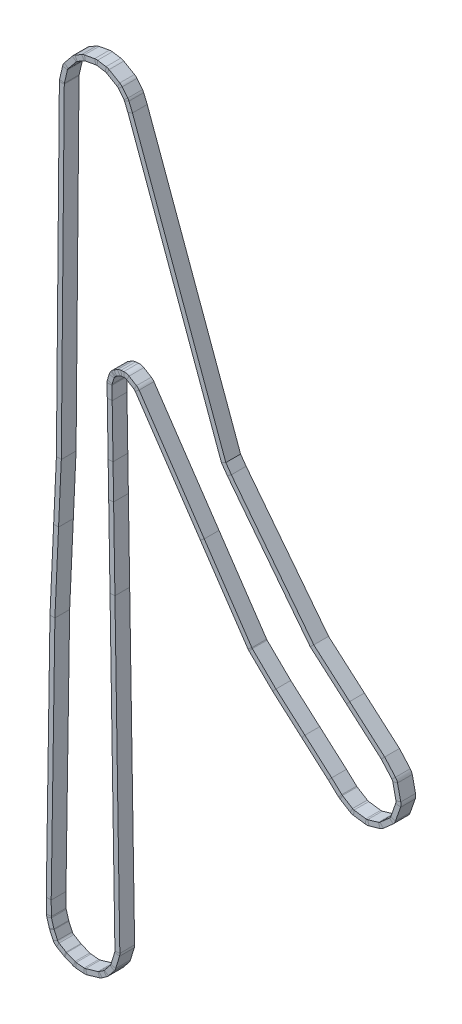
SolidWorks part; units mm, degrees
ref_plane "Front Plane" through (0, 0, 0) normal (0, 0, 1) x (1, 0, 0)
ref_plane "Top Plane" through (0, 0, 0) normal (0, 1, 0) x (1, 0, 0)
ref_plane "Right Plane" through (0, 0, 0) normal (1, 0, 0) x (0, 0, -1)
sketch "Sketch1" plane through (0, 0, 0) normal (0, 0, 1) x (1, 0, 0)
  line L0 (98.4655, -26.6334) -> (45.749, 19.1924)
  line L1 (45.749, 19.1924) -> (0.051, 81.6795)
  line L3 (-7.9905, 92.6754) -> (-68.2589, 257.4582)
  line L4 (-63.2016, 102.3497) -> (12.7547, -10.0268)
  line L5 (12.7547, -10.0268) -> (66.814, -57.6387)
  line L6 (-75.4614, -216.8683) -> (-75.4494, -217.5984)
  line L7 (-119.8994, -217.5984) -> (-117.4111, -51.9664)
  line L8 (-111.3567, 249.8241) -> (-113.2737, 38.7081)
  line L9 (-80.618, 97.0158) -> (-75.4494, -217.5984)
  arc A1 (66.814, -57.6387) -> (98.4655, -26.6334) centre (83.8846, -43.4068) ccw
  arc A2 (-7.9905, 92.6754) -> (0.051, 81.6795) centre (7.6048, 95.6421) ccw
  arc A3 (-68.2589, 257.4582) -> (-111.3567, 249.8241) centre (-89.1317, 249.8241) ccw
  arc A4 (-119.8894, -216.9308) -> (-75.4614, -216.8683) centre (-97.6744, -217.5984) ccw
  arc A5 (-63.2016, 102.3497) -> (-80.618, 97.0158) centre (-71.093, 97.0158) ccw
sketch "Sketch2" plane through (0, 0, 0) normal (0, 1, 0) x (1, 0, 0)
  line L0 (-116.641, -4.7695) -> (-113.466, 4.7555) construction
  line L1 (-113.466, -4.7695) -> (-116.641, -4.7695)
  line L2 (-113.466, -4.7695) -> (-113.466, 4.7555)
  line L3 (-113.466, 4.7555) -> (-116.641, 4.7555)
  line L4 (-116.641, -4.7695) -> (-116.641, 4.7555)
  line L5 (-113.466, -4.7695) -> (-116.641, 4.7555) construction
  dimension "D1" = 3.175
  dimension "D2" = 9.525
sketch "Sketch3" plane through (0, 0, 0) normal (0, 0, 1) x (1, 0, 0)
  line L0 (-113.2737, 38.7081) -> (-111.3607, 249.3794)
  line L1 (-111.2559, 250.2572) -> (-109.2845, 258.7288)
  line L2 (-108.485, 260.36) -> (-103.2826, 266.7567)
  line L3 (-102.1399, 267.7223) -> (-97.7053, 270.2323)
  line L4 (-96.4553, 270.6877) -> (-89.814, 271.9222)
  line L5 (-88.4462, 271.9406) -> (-83.0216, 271.0824)
  line L6 (-81.6152, 270.5801) -> (-74.7314, 266.5543)
  line L7 (-73.5978, 265.5668) -> (-70.0494, 261.0582)
  line L8 (-69.4933, 260.1093) -> (-67.2613, 254.7304)
  line L9 (-7.9905, 92.6754) -> (-68.2589, 257.4582) construction
  line L10 (-67.2613, 254.7304) -> (-6.9418, 89.285)
  line L11 (-6.9418, 89.285) -> (-3.231, 84.0404)
  line L12 (-3.231, 84.0404) -> (50.1017, 15.4087)
  line L13 (98.4655, -26.6334) -> (45.749, 19.1924) construction
  line L14 (50.1017, 15.4087) -> (73.3998, -4.8441)
  line L15 (73.3998, -4.8441) -> (95.8794, -24.3853)
  line L16 (95.8794, -24.3853) -> (102.8247, -32.2162)
  line L17 (103.7499, -34.0415) -> (105.8276, -43.6606)
  line L18 (105.6923, -45.8446) -> (102.428, -55.1766)
  line L19 (101.2968, -56.8629) -> (95.0555, -62.3984)
  line L20 (93.5133, -63.2516) -> (86.4539, -65.3208)
  line L21 (84.7719, -65.4465) -> (77.0991, -64.3963)
  line L22 (75.5267, -63.832) -> (68.9797, -59.7901)
  line L23 (68.3531, -59.3129) -> (61.7508, -53.1793)
  line L24 (12.7547, -10.0268) -> (66.814, -57.6387) construction
  line L25 (61.7508, -53.1793) -> (44.551, -38.0309)
  line L26 (44.551, -38.0309) -> (25.7851, -21.5031)
  line L27 (25.7851, -21.5031) -> (10.5331, -6.5929)
  line L28 (-63.2016, 102.3497) -> (12.7547, -10.0268) construction
  line L29 (10.0108, -5.9672) -> (-20.7003, 39.4696)
  line L30 (-20.7003, 39.4696) -> (-62.7161, 101.6314)
  line L31 (-63.9393, 102.8052) -> (-68.7289, 105.7621)
  line L32 (-71.1857, 106.3495) -> (-73.0015, 106.1972)
  line L33 (-74.6515, 105.6879) -> (-76.8626, 104.4364)
  line L34 (-77.9202, 103.5722) -> (-78.4276, 102.9884)
  line L35 (-79.241, 101.5208) -> (-80.4319, 97.6248)
  line L36 (-80.6076, 96.3791) -> (-80.4673, 87.8427)
  line L37 (-80.618, 97.0158) -> (-75.4494, -217.5984) construction
  line L38 (-80.4673, 87.8427) -> (-79.9113, 53.9988)
  line L39 (-79.9113, 53.9988) -> (-79.5449, 31.6929)
  line L40 (-79.5449, 31.6929) -> (-78.6908, -20.2959)
  line L41 (-78.6908, -20.2959) -> (-75.52, -218.5999)
  line L42 (-75.6957, -219.8437) -> (-78.1516, -227.8785)
  line L43 (-78.8798, -229.2448) -> (-82.5912, -233.8083)
  line L44 (-83.391, -234.5562) -> (-86.3383, -236.6415)
  line L45 (-87.5338, -237.2196) -> (-95.5395, -239.5663)
  line L46 (-97.0156, -239.7148) -> (-102.1926, -239.2755)
  line L47 (-103.3693, -238.9935) -> (-108.7869, -236.7939)
  line L48 (-109.3384, -236.5192) -> (-113.9073, -233.7895)
  line L49 (-115.5023, -232.0146) -> (-117.7346, -227.1706)
  line L50 (-117.9421, -226.6168) -> (-119.5306, -221.1976)
  line L51 (-119.6932, -220.1083) -> (-119.7978, -210.8362)
  line L52 (-119.8994, -217.5984) -> (-117.4111, -51.9664) construction
  line L53 (-119.7978, -210.8362) -> (-117.4111, -51.9664)
  line L54 (-113.2737, 38.7081) -> (-117.4111, -51.9664)
  arc A0 (-68.2589, 257.4582) -> (-111.3567, 249.8241) centre (-89.1317, 249.8241) ccw construction
  arc A1 (-7.9905, 92.6754) -> (0.051, 81.6795) centre (7.6048, 95.6421) ccw construction
  arc A2 (66.814, -57.6387) -> (98.4655, -26.6334) centre (83.8846, -43.4068) ccw construction
  arc A3 (-63.2016, 102.3497) -> (-80.618, 97.0158) centre (-71.093, 97.0158) ccw construction
  arc A4 (-119.8894, -216.9308) -> (-75.4614, -216.8683) centre (-97.6744, -217.5984) ccw construction
  arc A5 (-119.5306, -221.1976) -> (-119.6932, -220.1083) centre (-115.6589, -220.0628) cw
  arc A6 (-117.7346, -227.1706) -> (-117.9421, -226.6168) centre (-114.0704, -225.482) cw
  arc A7 (-113.9073, -233.7895) -> (-115.5023, -232.0146) centre (-111.838, -230.326) cw
  arc A8 (-108.7869, -236.7939) -> (-109.3384, -236.5192) centre (-107.2691, -233.0557) cw
  arc A9 (-102.1926, -239.2755) -> (-103.3693, -238.9935) centre (-101.8515, -235.2553) cw
  arc A10 (-95.5395, -239.5663) -> (-97.0156, -239.7148) centre (-96.6744, -235.6946) cw
  arc A11 (-86.3383, -236.6415) -> (-87.5338, -237.2196) centre (-88.6686, -233.3479) cw
  arc A12 (-82.5912, -233.8083) -> (-83.391, -234.5562) centre (-85.7214, -231.2627) cw
  arc A13 (-78.1516, -227.8785) -> (-78.8798, -229.2448) centre (-82.0099, -226.6991) cw
  arc A14 (-75.52, -218.5999) -> (-75.6957, -219.8437) centre (-79.5541, -218.6644) cw
  arc A15 (10.5331, -6.5929) -> (10.0108, -5.9672) centre (13.3534, -3.7079) cw
  arc A16 (68.9797, -59.7901) -> (68.3531, -59.3129) centre (71.0992, -56.357) cw
  arc A17 (77.0991, -64.3963) -> (75.5267, -63.832) centre (77.6462, -60.3989) cw
  arc A18 (86.4539, -65.3208) -> (84.7719, -65.4465) centre (85.319, -61.4491) cw
  arc A19 (95.0555, -62.3984) -> (93.5133, -63.2516) centre (92.3784, -59.3799) cw
  arc A20 (102.428, -55.1766) -> (101.2968, -56.8629) centre (98.6197, -53.8445) cw
  arc A21 (105.8276, -43.6606) -> (105.6923, -45.8446) centre (101.884, -44.5125) cw
  arc A22 (102.8247, -32.2162) -> (103.7499, -34.0415) centre (99.8062, -34.8933) cw
  arc A23 (-70.0494, 261.0582) -> (-69.4933, 260.1093) centre (-73.2198, 258.563) cw
  arc A24 (-74.7314, 266.5543) -> (-73.5978, 265.5668) centre (-76.7682, 263.0716) cw
  arc A25 (-83.0216, 271.0824) -> (-81.6152, 270.5801) centre (-83.652, 267.0974) cw
  arc A26 (-89.814, 271.9222) -> (-88.4462, 271.9406) centre (-89.0767, 267.9556) cw
  arc A27 (-97.7053, 270.2323) -> (-96.4553, 270.6877) centre (-95.718, 266.7211) cw
  arc A28 (-103.2826, 266.7567) -> (-102.1399, 267.7223) centre (-100.1525, 264.2111) cw
  arc A29 (-109.2845, 258.7288) -> (-108.485, 260.36) centre (-105.3549, 257.8143) cw
  arc A30 (-111.3607, 249.3794) -> (-111.2559, 250.2572) centre (-107.3263, 249.3428) cw
  arc A31 (-80.4319, 97.6248) -> (-80.6076, 96.3791) centre (-76.5735, 96.4454) ccw
  arc A32 (-78.4276, 102.9884) -> (-79.241, 101.5208) centre (-75.3827, 100.3415) ccw
  arc A33 (-76.8626, 104.4364) -> (-77.9202, 103.5722) centre (-74.8752, 100.9252) ccw
  arc A34 (-73.0015, 106.1972) -> (-74.6515, 105.6879) centre (-72.6641, 102.1767) ccw
  arc A35 (-62.7161, 101.6314) -> (-63.9393, 102.8052) centre (-66.0588, 99.3721) ccw
  arc A36 (-68.7289, 105.7621) -> (-71.1857, 106.3495) centre (-70.8484, 102.3291) ccw
  point P83 (-119.6869, -220.6642)
  point P86 (-117.8587, -226.9013)
  point P91 (-109.0732, -236.6777)
  point P94 (-102.8023, -239.2237)
  point P97 (-96.2637, -239.7786)
  point P100 (-86.8878, -237.0303)
  point P103 (-82.9399, -234.2371)
  point P106 (-78.3821, -228.6328)
  point P109 (-75.5098, -219.2356)
  point P112 (10.2402, -6.3066)
  point P115 (68.643, -59.5822)
  point P118 (76.2532, -64.2805)
  point P121 (85.6263, -65.5634)
  point P124 (94.3799, -62.9976)
  point P127 (102.0816, -56.1669)
  point P130 (106.0676, -44.7717)
  point P133 (103.5265, -33.0075)
  point P136 (-69.7061, 260.622)
  point P139 (-74.071, 266.1681)
  point P142 (-82.2711, 270.9637)
  point P145 (-89.1317, 272.0491)
  point P148 (-97.1184, 270.5645)
  point P151 (-102.8023, 267.3473)
  point P154 (-109.0732, 259.6367)
  point P157 (-111.3567, 249.8241)
  point P160 (-80.618, 97.0158)
  point P163 (-78.9903, 102.3411)
  point P166 (-77.4656, 104.0951)
  point P169 (-73.8823, 106.1233)
  point P172 (-63.2016, 102.3497)
  point P175 (-69.8605, 106.4607)
  dimension "D1" = 4.0346
sweep "Sweep2" add profiles "Sketch2" path "Sketch3"
